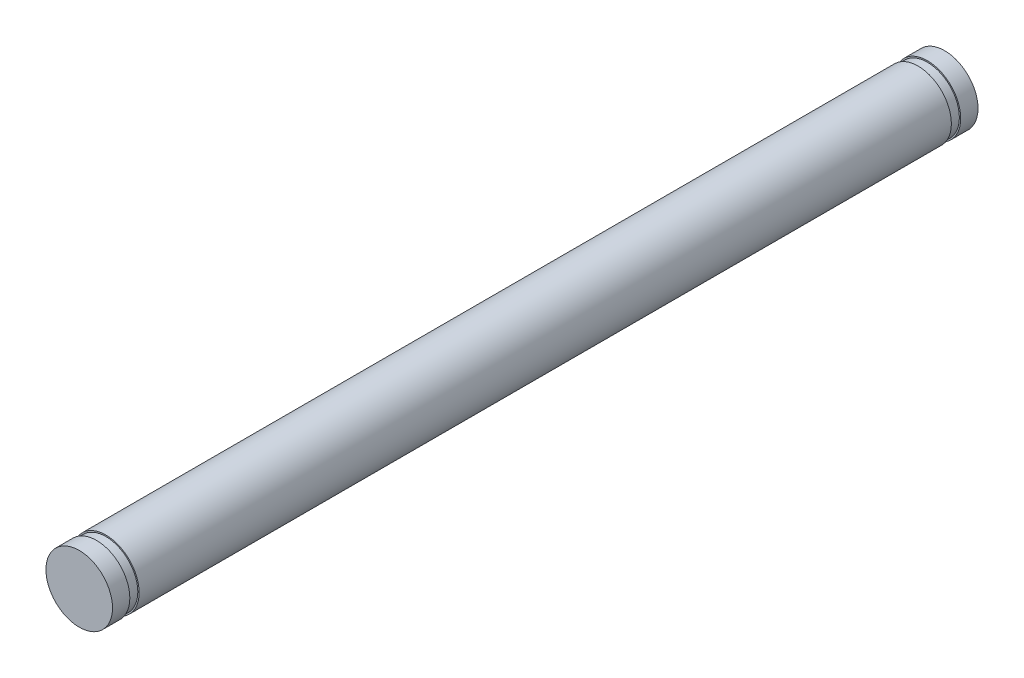
SolidWorks part; units mm, degrees
ref_plane "Płaszczyzna przednia" through (0, 0, 0) normal (0, 0, 1) x (1, 0, 0)
ref_plane "Płaszczyzna górna" through (0, 0, 0) normal (0, 1, 0) x (1, 0, 0)
ref_plane "Płaszczyzna prawa" through (0, 0, 0) normal (1, 0, 0) x (0, 0, -1)
sketch "Szkic1" plane through (0, 0, 0) normal (1, 0, 0) x (0, 0, -1)
  line L0 (-31.2, -2.5) -> (-31.2, -2.4)
  line L1 (-32.5, 0) -> (32.5, 0)
  line L2 (-32.5, 0) -> (-32.5, -2.5)
  line L3 (-32.5, -2.5) -> (-31.2, -2.5)
  line L4 (32.5, 0) -> (32.5, -2.5)
  line L5 (-31.2, -2.4) -> (-30.5, -2.4)
  line L6 (-30.5, -2.4) -> (-30.5, -2.5)
  line L7 (0, 0) -> (0, -12.913) construction
  line L8 (31.2, -2.5) -> (31.2, -2.4)
  line L9 (31.2, -2.4) -> (30.5, -2.4)
  line L10 (30.5, -2.4) -> (30.5, -2.5)
  line L11 (31.2, -2.5) -> (32.5, -2.5)
  line L12 (-30.5, -2.5) -> (30.5, -2.5)
  dimension "D1" = 65
  dimension "D2" = 2.5
  dimension "D3" = 0.7
  dimension "D4" = 0.1
  dimension "D5" = 61
revolve "Obrót1" add sketch "Szkic1" angle 360 about L1
